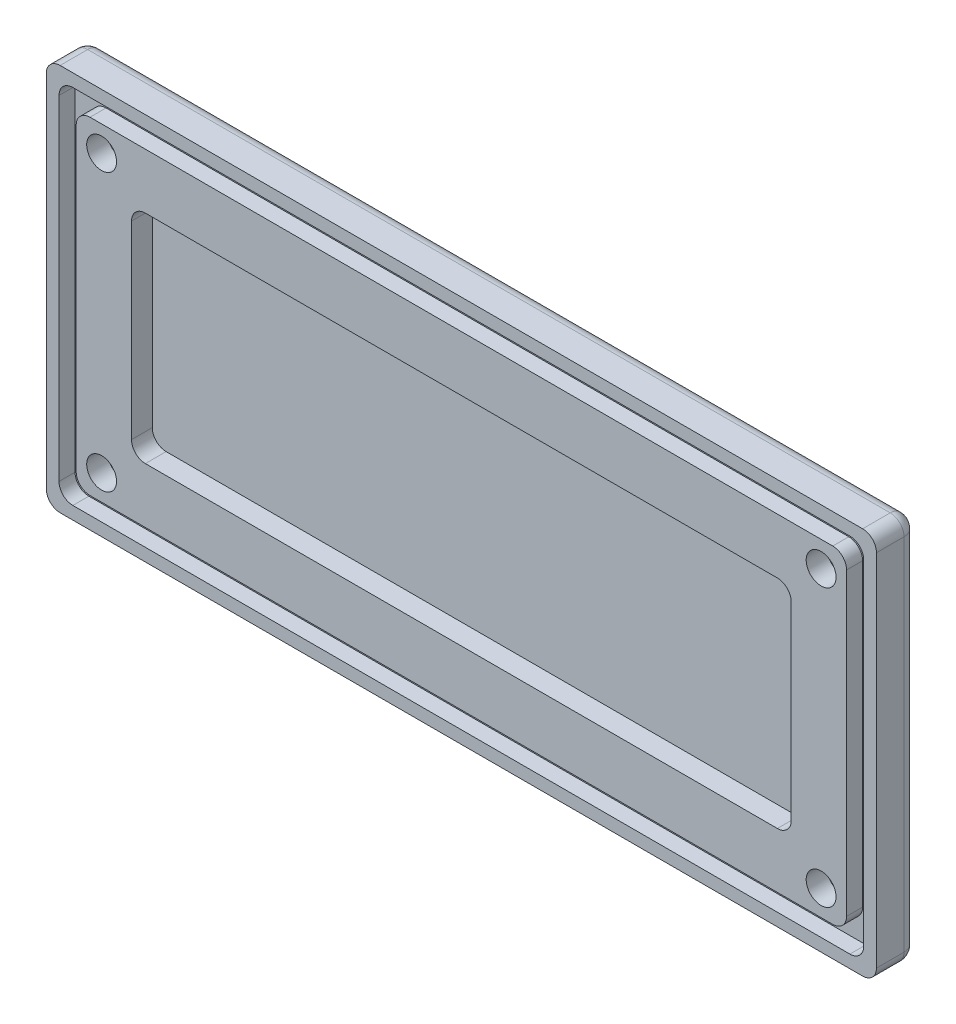
SolidWorks part; units mm, degrees
ref_plane "Front Plane" through (0, 0, 0) normal (0, 0, 1) x (1, 0, 0)
ref_plane "Top Plane" through (0, 0, 0) normal (0, 1, 0) x (1, 0, 0)
ref_plane "Right Plane" through (0, 0, 0) normal (1, 0, 0) x (0, 0, -1)
sketch "Sketch1" plane through (0, 0, 0) normal (0, 0, 1) x (1, 0, 0)
  line L1 (-47.625, -22.225) -> (47.625, -22.225)
  line L2 (-47.625, -22.225) -> (-47.625, 22.225)
  line L3 (-47.625, 22.225) -> (47.625, 22.225)
  line L4 (47.625, -22.225) -> (47.625, 22.225)
  line L5 (-47.625, -22.225) -> (47.625, 22.225) construction
  line L6 (-47.625, 22.225) -> (47.625, -22.225) construction
  point P0 (0, 0)
  dimension "D1" = 44.45
  dimension "D2" = 95.25
extrude "Boss-Extrude1" add sketch "Sketch1" along normal blind 4.75
sketch "Sketch2" plane through (0, 0, 4.75) normal (0, 0, 1) x (1, 0, 0)
  line L1 (-47.625, -22.225) -> (47.625, -22.225)
  line L2 (-47.625, -22.225) -> (-47.625, 22.225)
  line L3 (-47.625, 22.225) -> (47.625, 22.225)
  line L4 (47.625, -22.225) -> (47.625, 22.225)
  line L5 (-47.625, -22.225) -> (47.625, 22.225) construction
  line L6 (-47.625, 22.225) -> (47.625, -22.225) construction
  line L7 (-44.5775, -20.765) -> (44.5775, -20.765)
  line L8 (-46.165, -19.1775) -> (-46.165, 19.1775)
  line L9 (-44.5775, 20.765) -> (44.5775, 20.765)
  line L10 (46.165, -19.1775) -> (46.165, 19.1775)
  line L11 (-46.165, -20.765) -> (46.165, 20.765) construction
  line L12 (-46.165, 20.765) -> (46.165, -20.765) construction
  line L17 (-42.6075, -18.795) -> (42.6075, -18.795)
  line L18 (-44.195, -17.2075) -> (-44.195, 17.2075)
  line L23 (-42.6075, 18.795) -> (42.6075, 18.795)
  line L24 (44.195, -17.2075) -> (44.195, 17.2075)
  line L25 (-44.195, -18.795) -> (44.195, 18.795) construction
  line L26 (-44.195, 18.795) -> (44.195, -18.795) construction
  arc A0 (44.5775, 20.765) -> (46.165, 19.1775) centre (44.5775, 19.1775) cw
  arc A1 (42.6075, 18.795) -> (44.195, 17.2075) centre (42.6075, 17.2075) cw
  arc A2 (42.6075, -18.795) -> (44.195, -17.2075) centre (42.6075, -17.2075) ccw
  arc A3 (44.5775, -20.765) -> (46.165, -19.1775) centre (44.5775, -19.1775) ccw
  arc A4 (-42.6075, -18.795) -> (-44.195, -17.2075) centre (-42.6075, -17.2075) cw
  arc A5 (-44.5775, -20.765) -> (-46.165, -19.1775) centre (-44.5775, -19.1775) cw
  arc A6 (-44.195, 17.2075) -> (-42.6075, 18.795) centre (-42.6075, 17.2075) cw
  arc A7 (-46.165, 19.1775) -> (-44.5775, 20.765) centre (-44.5775, 19.1775) cw
  point P0 (0, 0)
  point P7 (0, 0)
  point P12 (0, 0)
  point P13 (0, 0)
  point P17 (0, 0)
  dimension "D5" = 1.5875
  dimension "D1" = 1.46
  dimension "D2" = 1.46
  dimension "D3" = 3.43
  dimension "D4" = 3.43
extrude "Cut-Extrude1" cut sketch "Sketch2" against normal blind 1.84 contours A7 L8 A5 L7 A3 L10 A0 L9 L18 A6 L23 A1 L24 A2 L17 A4
sketch "Sketch3" plane through (0, 0, 4.75) normal (0, 0, 1) x (1, 0, 0)
  line L0 (47.625, -22.225) -> (47.625, 22.225) construction
  line L1 (-36.2575, 12.445) -> (36.2575, 12.445)
  line L2 (-37.845, 10.8575) -> (-37.845, -10.8575)
  line L3 (-36.2575, -12.445) -> (36.2575, -12.445)
  line L4 (37.845, 10.8575) -> (37.845, -10.8575)
  line L5 (-37.845, 12.445) -> (37.845, -12.445) construction
  line L6 (-37.845, -12.445) -> (37.845, 12.445) construction
  line L7 (47.625, 22.225) -> (-47.625, 22.225) construction
  arc A0 (-37.845, -10.8575) -> (-36.2575, -12.445) centre (-36.2575, -10.8575) ccw
  arc A1 (-36.2575, 12.445) -> (-37.845, 10.8575) centre (-36.2575, 10.8575) ccw
  arc A2 (36.2575, -12.445) -> (37.845, -10.8575) centre (36.2575, -10.8575) ccw
  arc A3 (36.2575, 12.445) -> (37.845, 10.8575) centre (36.2575, 10.8575) cw
  point P0 (0, 0)
  dimension "D3" = 1.5875
  dimension "D1" = 9.78
  dimension "D2" = 9.78
extrude "Cut-Extrude2" cut sketch "Sketch3" against normal blind 2.38
sketch "Sketch4" plane through (0, 0, 4.75) normal (0, 0, 1) x (1, 0, 0)
  line L0 (47.625, 22.225) -> (-47.625, 22.225) construction
  line L1 (-47.625, 22.225) -> (-47.625, -22.225) construction
  circle A0 centre (-41.275, 15.875) radius 1.715
  dimension "D1" = 3.43
  dimension "D2" = 6.35
  dimension "D3" = 6.35
extrude "Cut-Extrude3" cut sketch "Sketch4" against normal through all
sketch "Sketch5" plane through (0, 0, 0) normal (0, 0, -1) x (-1, 0, 0)
  circle A0 centre (41.275, 15.875) radius 3.05
  dimension "D1" = 6.1
extrude "Cut-Extrude4" cut sketch "Sketch5" against normal blind 2.38
mirror "Mirror1" about plane through (0, 0, 0) normal (1, 0, 0) of "Cut-Extrude4", "Cut-Extrude3" second plane through (0, 0, 0) second plane normal (0, 1, 0)
fillet "Fillet1" radius 1.5875 8 edges at (-47.625, -22.225, 2.375) (0, -22.225, 0) (47.625, -22.225, 2.375) (47.625, 0, 0) (47.625, 22.225, 2.375) (-47.625, 0, 0) (0, 22.225, 0) (-47.625, 22.225, 2.375)
